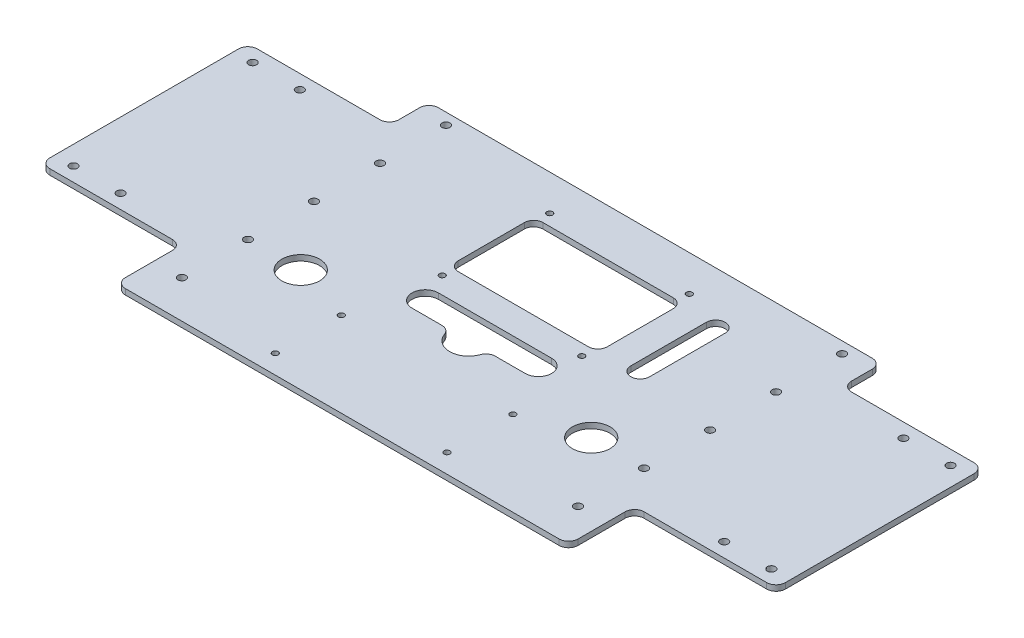
SolidWorks part; units mm, degrees
material "Thornel Mat VMA"
ref_plane "前视基准面" through (0, 0, 0) normal (0, 0, 1) x (1, 0, 0)
ref_plane "上视基准面" through (0, 0, 0) normal (0, 1, 0) x (1, 0, 0)
ref_plane "右视基准面" through (0, 0, 0) normal (1, 0, 0) x (0, 0, -1)
sketch "草图1" plane through (0, 0, 0) normal (0, 1, 0) x (1, 0, 0)
  line L0 (31.5759, -198.8718) -> (31.5759, 46.1282) construction
  line L1 (151.5759, -32.8718) -> (-88.4241, -32.8718)
  line L7 (-88.4241, -198.8718) -> (151.5759, -198.8718)
  line L8 (-88.4241, -198.8718) -> (-88.4241, -32.8718)
  line L10 (151.5759, -198.8718) -> (151.5759, -32.8718)
  line L16 (6.5759, -59.8718) -> (56.5759, -59.8718) construction
  line L18 (6.5759, -34.8718) -> (6.5759, -84.8718) construction
  line L19 (6.5759, -84.8718) -> (56.5759, -84.8718) construction
  line L20 (56.5759, -34.8718) -> (56.5759, -84.8718) construction
  line L21 (151.5759, -94.8718) -> (-88.4241, -94.8718) construction
  line L22 (-88.4241, -49.8718) -> (151.5759, -49.8718) construction
  circle A5 centre (6.5759, -84.8718) radius 1.6 construction
  circle A6 centre (56.5759, -84.8718) radius 1.6 construction
  point P6 (0, -121.2547)
  dimension "D2" = 166
  dimension "D4" = 240
  dimension "D9" = 10
  dimension "D12" = 50
  dimension "D15" = 45
extrude "构型与裁判孔" add sketch "草图1" along normal blind 3 contours L10 L21 L8 L7
sketch "草图4" plane through (0, 3, 0) normal (0, 1, 0) x (1, 0, 0)
  line L0 (-73.4241, -108.8718) -> (-73.4241, -198.8718) construction
  line L1 (77.0759, -32.8718) -> (77.0759, -198.8718) construction
  line L2 (151.5759, -32.8718) -> (-88.4241, -32.8718) construction
  line L3 (-88.4241, -198.8718) -> (-88.4241, -32.8718) construction
  line L4 (31.5759, -32.8718) -> (31.5759, -198.8718) construction
  line L5 (-88.4241, -198.8718) -> (151.5759, -198.8718) construction
  line L6 (-13.9241, -32.8718) -> (-13.9241, -198.8718) construction
  line L7 (-88.4241, -198.8718) -> (151.5759, -198.8718) construction
  line L8 (-88.4241, -198.8718) -> (151.5759, -198.8718) construction
  circle A0 centre (-73.4241, -73.8718) radius 2.1
  circle A1 centre (136.5759, -178.8718) radius 2.1
  circle A2 centre (-73.4241, -108.8718) radius 2.1
  circle A3 centre (-73.4241, -143.8718) radius 2.1
  circle A4 centre (-73.4241, -178.8718) radius 2.1
  circle A5 centre (136.5759, -143.8718) radius 2.1
  circle A6 centre (136.5759, -108.8718) radius 2.1
  circle A7 centre (136.5759, -73.8718) radius 2.1
  circle A8 centre (-73.4241, -38.8718) radius 2.1
  circle A9 centre (136.5759, -38.8718) radius 2.1
  circle A10 centre (77.0759, -188.8718) radius 1.55
  circle A11 centre (-13.9241, -188.8718) radius 1.55
  circle A12 centre (77.0759, -153.8718) radius 1.55
  circle A13 centre (-13.9241, -153.8718) radius 1.55
  dimension "D2" = 20
  dimension "D5" = 35
  dimension "D6" = 35
  dimension "D7" = 35
  dimension "D3" = 4.2
  dimension "D4" = 35
  dimension "D8" = 3.1
  dimension "D9" = 10
  dimension "D10" = 35
  dimension "D1" = 15
  dimension "D11" = 91
extrude "切除-拉伸3" cut sketch "草图4" against normal through all
sketch "草图5" plane through (0, 3, 0) normal (0, 1, 0) x (1, 0, 0)
  line L0 (71.0759, -57.8718) -> (-7.9241, -57.8718)
  line L1 (71.0759, -57.8718) -> (71.0759, -102.8718)
  line L2 (71.0759, -102.8718) -> (-7.9241, -102.8718)
  line L3 (-7.9241, -57.8718) -> (-7.9241, -102.8718)
  line L4 (71.0759, -57.8718) -> (-7.9241, -102.8718) construction
  line L5 (71.0759, -102.8718) -> (-7.9241, -57.8718) construction
  line L6 (31.5759, -32.8718) -> (31.5759, -104.1535) construction
  line L7 (71.0759, -80.3718) -> (-7.9241, -80.3718) construction
  line L8 (31.5759, -57.8718) -> (31.5759, -102.8718) construction
  line L9 (151.5759, -32.8718) -> (-88.4241, -32.8718) construction
  line L10 (91.0759, -100.3718) -> (91.0759, -60.3718) construction
  line L11 (86.0759, -100.3718) -> (86.0759, -60.3718)
  line L12 (96.0759, -100.3718) -> (96.0759, -60.3718)
  line L13 (31.5759, -102.8718) -> (31.5759, -198.8718) construction
  line L16 (-88.4241, -198.8718) -> (151.5759, -198.8718) construction
  line L17 (1.5759, -124.8718) -> (61.5759, -124.8718) construction
  line L18 (1.5759, -117.8718) -> (61.5759, -117.8718)
  line L19 (1.5759, -131.8718) -> (21.5759, -131.8718)
  line L20 (41.5759, -131.8718) -> (61.5759, -131.8718)
  line L21 (-73.4241, -143.8718) -> (136.5759, -143.8718) construction
  circle A0 centre (-5.4241, -51.8718) radius 1.55
  circle A1 centre (68.5759, -51.8718) radius 1.55
  circle A2 centre (68.5759, -108.8718) radius 1.55
  circle A3 centre (-5.4241, -108.8718) radius 1.55
  arc A4 (86.0759, -100.3718) -> (96.0759, -100.3718) centre (91.0759, -100.3718) ccw
  arc A5 (96.0759, -60.3718) -> (86.0759, -60.3718) centre (91.0759, -60.3718) ccw
  arc A8 (1.5759, -117.8718) -> (1.5759, -131.8718) centre (1.5759, -124.8718) ccw
  arc A9 (61.5759, -131.8718) -> (61.5759, -117.8718) centre (61.5759, -124.8718) ccw
  arc A10 (21.5759, -131.8718) -> (41.5759, -131.8718) centre (31.5759, -131.8718) ccw
  circle A11 centre (-45.4241, -143.8718) radius 10
  circle A12 centre (-73.4241, -143.8718) radius 2.1 construction
  circle A13 centre (108.5759, -143.8718) radius 10
  point P1 (110.5236, -62.9669)
  point P23 (91.0759, -80.3718)
  point P33 (31.5759, -124.8718)
  dimension "D3" = 3.1
  dimension "D7" = 5
  dimension "D10" = 7
  dimension "D13" = 20
  dimension "D14" = 28
  dimension "D1" = 79
  dimension "D2" = 45
  dimension "D4" = 37
  dimension "D5" = 28.5
  dimension "D6" = 25
  dimension "D8" = 40
  dimension "D9" = 15
  dimension "D11" = 60
  dimension "D12" = 15
extrude "切除-拉伸4" cut sketch "草图5" against normal through all
sketch "草图6" plane through (0, 0, 0) normal (0, 1, 0) x (1, 0, 0)
  line L0 (-63.0381, -108.8718) -> (146.9619, -108.8718) construction
  line L1 (-88.4241, -53.8718) -> (-163.4241, -53.8718)
  line L2 (-88.4241, -198.8718) -> (-88.4241, -32.8718) construction
  line L3 (-163.4241, -53.8718) -> (-163.4241, -163.8718)
  line L4 (-73.4241, -108.8718) -> (136.5759, -108.8718) construction
  line L5 (-88.4241, -53.8718) -> (-88.4241, -163.8718)
  line L6 (-88.4241, -163.8718) -> (-163.4241, -163.8718)
  line L7 (31.5759, -32.8718) -> (31.5759, -198.8718) construction
  line L8 (151.5759, -32.8718) -> (-88.4241, -32.8718) construction
  line L9 (-88.4241, -198.8718) -> (151.5759, -198.8718) construction
  line L10 (151.5759, -53.8718) -> (151.5759, -163.8718)
  line L11 (151.5759, -163.8718) -> (226.5759, -163.8718)
  line L12 (226.5759, -53.8718) -> (226.5759, -163.8718)
  line L13 (151.5759, -53.8718) -> (226.5759, -53.8718)
  line L14 (-153.4241, -53.8718) -> (-153.4241, -163.8718) construction
  line L15 (-128.4241, -53.8718) -> (-128.4241, -163.8718) construction
  line L16 (-153.4241, -61.3718) -> (-128.4241, -61.3718) construction
  circle A0 centre (-153.4241, -61.3718) radius 2.1
  circle A1 centre (-153.4241, -156.3718) radius 2.1
  circle A2 centre (216.5759, -156.3718) radius 2.1
  circle A3 centre (216.5759, -61.3718) radius 2.1
  circle A4 centre (-128.4241, -61.3718) radius 2.1
  circle A5 centre (-128.4241, -156.3718) radius 2.1
  circle A6 centre (191.5759, -156.3718) radius 2.1
  circle A7 centre (191.5759, -61.3718) radius 2.1
  point P15 (-88.4241, -108.8718)
  point P16 (-163.4241, -108.8718)
  dimension "D4" = 95
  dimension "D6" = 4.2
  dimension "D7" = 4.2
  dimension "D1" = 75
  dimension "D2" = 55
  dimension "D3" = 10
  dimension "D5" = 25
extrude "凸台-拉伸1" add sketch "草图6" along normal blind 3
fillet "圆角1" radius 5 18 edges at (71.0759, 1.5, 102.8718) (-7.9241, 1.5, 102.8718) (-7.9241, 1.5, 57.8718) (71.0759, 1.5, 57.8718) (151.5759, 1.5, 32.8718) (-88.4241, 1.5, 32.8718) (151.5759, 1.5, 53.8718) (151.5759, 1.5, 163.8718) (-88.4241, 1.5, 163.8718) (-88.4241, 1.5, 53.8718) (226.5759, 1.5, 53.8718) (226.5759, 1.5, 163.8718) (151.5759, 1.5, 198.8718) (-88.4241, 1.5, 198.8718) (-163.4241, 1.5, 53.8718) (-163.4241, 1.5, 163.8718) (41.5759, 1.5, 131.8718) (21.5759, 1.5, 131.8718)
